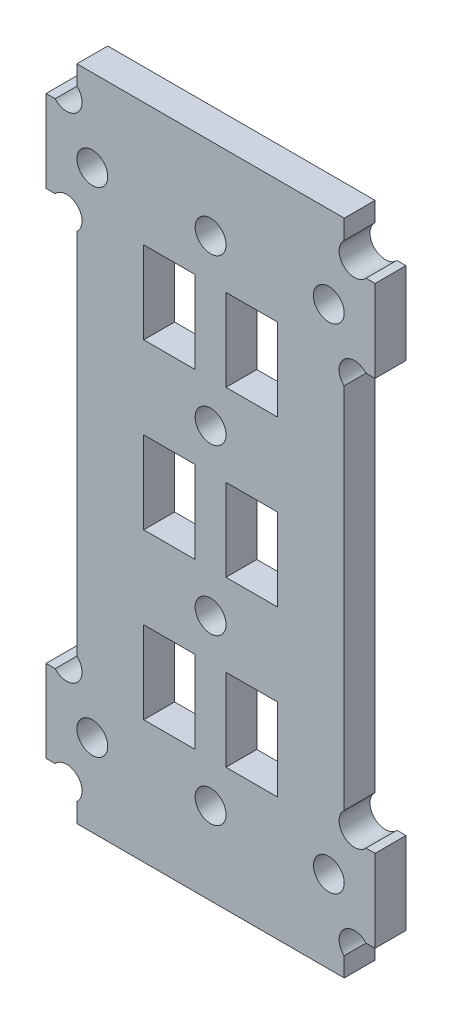
SolidWorks part; units mm, degrees
material "Thornel Mat VMA"
ref_plane "前视基准面" through (0, 0, 0) normal (0, 0, 1) x (1, 0, 0)
ref_plane "上视基准面" through (0, 0, 0) normal (0, 1, 0) x (1, 0, 0)
ref_plane "右视基准面" through (0, 0, 0) normal (1, 0, 0) x (0, 0, -1)
sketch "草图1" plane through (0, 0, 0) normal (0, 0, 1) x (1, 0, 0)
  line L1 (-16, -32) -> (16, -32)
  line L2 (-16, -32) -> (-16, 32)
  line L3 (-16, 32) -> (16, 32)
  line L4 (16, -32) -> (16, 32)
  line L5 (-16, -32) -> (16, 32) construction
  line L6 (-16, 32) -> (16, -32) construction
  point P0 (0, 0)
  dimension "D1" = 32
  dimension "D2" = 64
extrude "凸台-拉伸1" add sketch "草图1" along normal blind 3
sketch "草图2" plane through (0, 0, 3) normal (0, 0, 1) x (1, 0, 0)
  line L1 (-4, -16) -> (4, -16)
  line L2 (-4, -16) -> (-4, 16)
  line L3 (-4, 16) -> (4, 16)
  line L4 (4, -16) -> (4, 16)
  line L5 (-4, -16) -> (4, 16) construction
  line L6 (-4, 16) -> (4, -16) construction
  line L7 (1.5, 12) -> (6.5, 12)
  line L8 (1.5, 12) -> (1.5, 20)
  line L9 (1.5, 20) -> (6.5, 20)
  line L10 (6.5, 12) -> (6.5, 20)
  line L11 (1.5, 12) -> (6.5, 20) construction
  line L12 (1.5, 20) -> (6.5, 12) construction
  point P0 (0, 0)
  dimension "D1" = 5
  dimension "D2" = 8
  dimension "D3" = 8
  dimension "D4" = 32
extrude "切除-拉伸1" cut sketch "草图2" against normal through all contours L7 L10 L9 L8 L3 L4 | L8 L7 L4 L3
mirror "镜向1" about plane through (0, 0, 0) normal (1, 0, 0) of "切除-拉伸1"
mirror "镜向2" about plane through (0, 0, 0) normal (0, 1, 0) of "镜向1", "切除-拉伸1"
sketch "草图4" plane through (0, 0, 3) normal (0, 0, 1) x (1, 0, 0)
  line L0 (16, -32) -> (16, 32) construction
  line L1 (16, -4) -> (13, -4)
  line L2 (16, -4) -> (16, 4)
  line L3 (16, 4) -> (13, 4)
  line L4 (13, -4) -> (13, 4)
  point P6 (13, 0)
  dimension "D1" = 3
  dimension "D2" = 8
extrude "切除-拉伸3" cut sketch "草图4" against normal blind 10
mirror "镜向5" about plane through (0, 0, 0) normal (1, 0, 0) of "切除-拉伸3"
sketch "草图6" plane through (0, 0, 3) normal (0, 0, 1) x (1, 0, 0)
  line L1 (16, 32) -> (13, 32)
  line L2 (16, 32) -> (16, 28)
  line L3 (16, 28) -> (13, 28)
  line L4 (13, 32) -> (13, 28)
  dimension "D1" = 3
  dimension "D2" = 28
extrude "切除-拉伸5" cut sketch "草图6" against normal through all
mirror "镜向8" about plane through (0, 0, 0) normal (0, 1, 0) of "切除-拉伸5"
mirror "镜向9" about plane through (0, 0, 0) normal (1, 0, 0) of "镜向8", "切除-拉伸5"
sketch "草图8" plane through (0, 0, 3) normal (0, 0, 1) x (1, 0, 0)
  line L0 (13, 28) -> (16, 28) construction
  line L2 (13, 32) -> (13, 28) construction
  circle A0 centre (14, 29) radius 1.5
  dimension "D3" = 3
  dimension "D1" = 1
  dimension "D2" = 1
extrude "切除-拉伸6" cut sketch "草图8" against normal through all
mirror "镜向10" about plane through (0, 0, 0) normal (1, 0, 0) of "切除-拉伸6"
mirror "镜向11" about plane through (0, 0, 0) normal (0, 1, 0) of "镜向10", "切除-拉伸6"
sketch "草图10" plane through (0, 0, 3) normal (0, 0, 1) x (1, 0, 0)
  line L0 (-16, 4) -> (-13, 4) construction
  line L1 (-13, 4) -> (-13, -4) construction
  circle A0 centre (-14, 3) radius 1.5
  point P6 (-13, 0)
  dimension "D1" = 1
  dimension "D2" = 1
  dimension "D3" = 3
extrude "切除-拉伸8" cut sketch "草图10" against normal through all
mirror "镜向14" about plane through (0, 0, 0) normal (0, 1, 0) of "切除-拉伸8"
mirror "镜向15" about plane through (0, 0, 0) normal (1, 0, 0) of "镜向14", "切除-拉伸8"
sketch "草图11" plane through (0, 0, 3) normal (0, 0, 1) x (1, 0, 0)
  circle A0 centre (-11.5, 8) radius 1.5
  circle A1 centre (-11.5, 24) radius 1.5
  dimension "D1" = 3
  dimension "D2" = 3
  dimension "D3" = 16
  dimension "D4" = 8
  dimension "D5" = 11.5
extrude "切除-拉伸9" cut sketch "草图11" against normal through all
mirror "镜向16" about plane through (0, 0, 0) normal (1, 0, 0) of "切除-拉伸9"
mirror "镜向17" about plane through (0, 0, 0) normal (0, 1, 0) of "镜向16", "切除-拉伸9"
sketch "草图12" plane through (0, 0, 0) normal (0, 0, -1) x (-1, 0, 0)
  line L0 (-16, 4) -> (-16, 28) construction
  line L1 (-16, 12) -> (-13, 12)
  line L2 (-16, 12) -> (-16, 20)
  line L3 (-16, 20) -> (-13, 20)
  line L4 (-13, 12) -> (-13, 20)
  dimension "D1" = 8
  dimension "D2" = 3
  dimension "D3" = 12
extrude "切除-拉伸10" cut sketch "草图12" against normal through all
mirror "镜向18" about plane through (0, 0, 0) normal (1, 0, 0) of "切除-拉伸10"
mirror "镜向19" about plane through (0, 0, 0) normal (0, 1, 0) of "切除-拉伸10", "镜向18"
sketch "草图13" plane through (0, 0, 0) normal (0, 0, -1) x (-1, 0, 0)
  line L0 (-16, 12) -> (-13, 12) construction
  line L1 (-13, 12) -> (-13, 20) construction
  line L2 (-13, 20) -> (-16, 20) construction
  circle A0 centre (-14, 19) radius 1.5
  circle A1 centre (-14, 13) radius 1.5
  dimension "D1" = 3
  dimension "D2" = 1
  dimension "D3" = 1
  dimension "D4" = 1
  dimension "D5" = 1
  dimension "D6" = 3
extrude "切除-拉伸11" cut sketch "草图13" against normal through all
mirror "镜向20" about plane through (0, 0, 0) normal (1, 0, 0) of "切除-拉伸11"
mirror "镜向21" about plane through (0, 0, 0) normal (0, 1, 0) of "镜向20", "切除-拉伸11"
sketch "草图14" plane through (0, 0, 0) normal (0, 0, -1) x (-1, 0, 0)
  line L1 (1.5, -4) -> (6.5, -4)
  line L2 (1.5, -4) -> (1.5, 4)
  line L3 (1.5, 4) -> (6.5, 4)
  line L4 (6.5, -4) -> (6.5, 4)
  line L5 (1.5, -4) -> (6.5, 4) construction
  line L6 (1.5, 4) -> (6.5, -4) construction
  point P0 (4, 0)
  dimension "D1" = 8
  dimension "D2" = 5
  dimension "D3" = 1.5
extrude "切除-拉伸12" cut sketch "草图14" against normal through all
mirror "镜向22" about plane through (0, 0, 0) normal (1, 0, 0) of "切除-拉伸12"
sketch "草图15" plane through (0, 0, 0) normal (0, 0, -1) x (-1, 0, 0)
  circle A0 centre (0, 8) radius 1.5
  circle A1 centre (0, 24) radius 1.5
  dimension "D1" = 3
  dimension "D2" = 3
  dimension "D3" = 8
  dimension "D4" = 24
extrude "切除-拉伸13" cut sketch "草图15" against normal through all
mirror "镜向23" about plane through (0, 0, 0) normal (0, 1, 0) of "切除-拉伸13"
sketch "草图16" plane through (0, 0, 0) normal (0, 0, -1) x (-1, 0, 0)
  circle A0 centre (-11.5, 8) radius 1.5
  circle A1 centre (11.5, 8) radius 1.5
  circle A2 centre (11.5, -8) radius 1.5
  circle A3 centre (-11.5, -8) radius 1.5
extrude "凸台-拉伸2" add sketch "草图16" against normal up to surface (3 mm away) up to face at (-1.5, -24, 3)
sketch "草图17" plane through (0, 0, 0) normal (0, 0, -1) x (-1, 0, 0)
  circle A0 centre (14, 13) radius 1.5
  circle A1 centre (-14, 13) radius 1.5
  circle A2 centre (-14, 3) radius 1.5
  circle A3 centre (14, 3) radius 1.5
  circle A4 centre (14, -3) radius 1.5
  circle A5 centre (-14, -3) radius 1.5
  circle A6 centre (-14, -13) radius 1.5
  circle A7 centre (14, -13) radius 1.5
extrude "凸台-拉伸3" add sketch "草图17" against normal up to surface (3 mm away) up to face at (-1.5, -24, 3)
sketch "草图18" plane through (0, 0, 0) normal (0, 0, -1) x (-1, 0, 0)
  line L0 (13, 14.118) -> (13, 17.882) construction
  line L1 (13, 15.3085) -> (16.4527, 15.3085)
  line L2 (13, 15.3085) -> (13, -15.1244)
  line L3 (13, -15.1244) -> (16.4527, -15.1244)
  line L4 (16.4527, 15.3085) -> (16.4527, -15.1244)
  line L5 (-13, 14.118) -> (-13, 17.882) construction
  line L6 (-13, 15.3085) -> (-16.8153, 15.3085)
  line L7 (-13, 15.3085) -> (-13, -15.1244)
  line L8 (-13, -15.1244) -> (-16.8153, -15.1244)
  line L9 (-16.8153, 15.3085) -> (-16.8153, -15.1244)
extrude "切除-拉伸14" cut sketch "草图18" against normal through all
